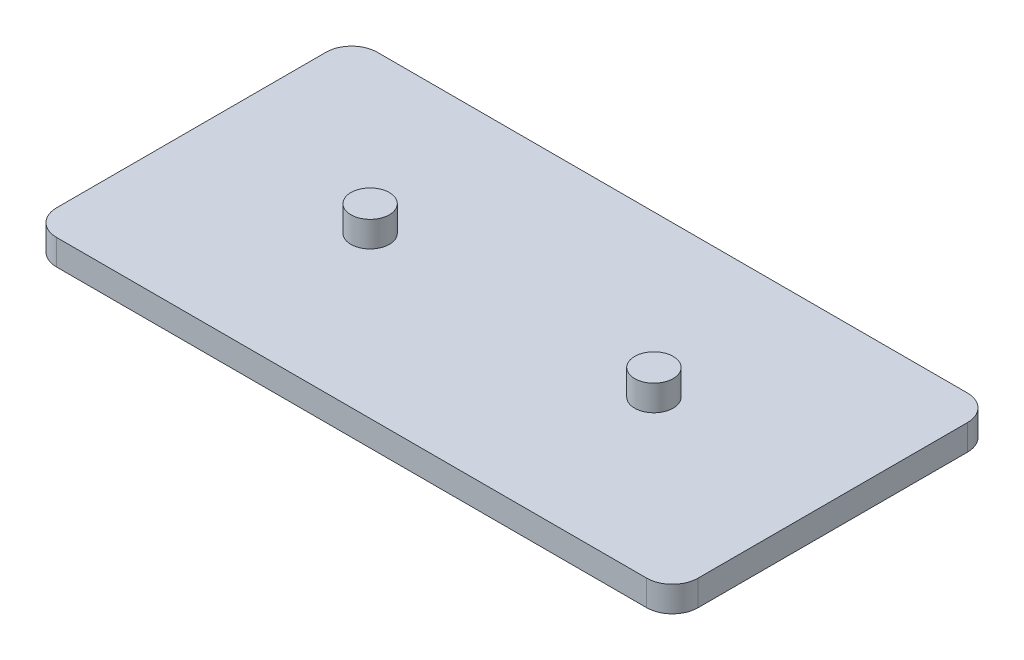
SolidWorks part; units mm, degrees
ref_plane "Front Plane" through (0, 0, 0) normal (0, 0, 1) x (1, 0, 0)
ref_plane "Top Plane" through (0, 0, 0) normal (0, 1, 0) x (1, 0, 0)
ref_plane "Right Plane" through (0, 0, 0) normal (1, 0, 0) x (0, 0, -1)
sketch "Sketch1" plane through (0, 0, 0) normal (0, 1, 0) x (1, 0, 0)
  line L1 (-317.5, 158.75) -> (317.5, 158.75)
  line L2 (-317.5, 158.75) -> (-317.5, -158.75)
  line L3 (-317.5, -158.75) -> (317.5, -158.75)
  line L4 (317.5, 158.75) -> (317.5, -158.75)
  line L5 (-317.5, 158.75) -> (317.5, -158.75) construction
  line L6 (-317.5, -158.75) -> (317.5, 158.75) construction
  point P0 (0, 0)
  dimension "D1" = 317.5
  dimension "D2" = 635
extrude "Boss-Extrude1" add sketch "Sketch1" along normal blind 25.4
sketch "Sketch2" plane through (0, 25.4, 0) normal (0, 1, 0) x (1, 0, 0)
  line L0 (0, 0) -> (-140.462, 0) construction
  line L1 (0, -158.75) -> (0, 158.75) construction
  line L2 (-317.5, -158.75) -> (317.5, -158.75) construction
  line L3 (317.5, 158.75) -> (-317.5, 158.75) construction
  circle A0 centre (-140.462, 0) radius 19.05
  circle A1 centre (140.462, 0) radius 19.05
  dimension "D2" = 38.1
  dimension "D1" = 140.462
extrude "Boss-Extrude2" add sketch "Sketch2" along normal blind 25.4
fillet "Fillet1" radius 25.4 4 edges at (-317.5, 12.7, 158.75) (-317.5, 12.7, -158.75) (317.5, 12.7, -158.75) (317.5, 12.7, 158.75)
